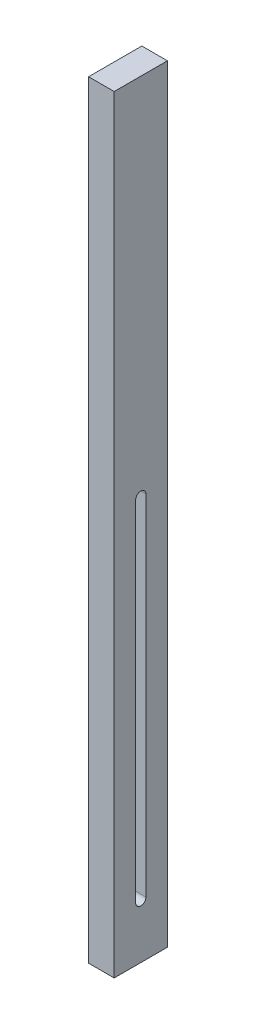
SolidWorks part; units mm, degrees
ref_plane "Front Plane" through (0, 0, 0) normal (0, 0, 1) x (1, 0, 0)
ref_plane "Top Plane" through (0, 0, 0) normal (0, 1, 0) x (1, 0, 0)
ref_plane "Right Plane" through (0, 0, 0) normal (1, 0, 0) x (0, 0, -1)
sketch "Sketch1" plane through (0, 0, 0) normal (0, 1, 0) x (1, 0, 0)
  line L1 (-101.2376, 21.9059) -> (-76.2376, 21.9059)
  line L2 (-101.2376, 21.9059) -> (-101.2376, -30.0941)
  line L3 (-101.2376, -30.0941) -> (-76.2376, -30.0941)
  line L4 (-76.2376, 21.9059) -> (-76.2376, -30.0941)
  dimension "D1" = 25
  dimension "D2" = 52
extrude "Boss-Extrude1" add sketch "Sketch1" along normal blind 750
sketch "Sketch3" plane through (-101.2376, 0, 0) normal (-1, 0, 0) x (0, 0, 1)
  line L0 (-21.9059, 750) -> (30.0941, 750)
  line L1 (4.0941, 750) -> (4.0941, 0)
  line L2 (-21.9059, 0) -> (30.0941, 0) construction
  line L3 (-0.9059, 394) -> (-0.9059, 53)
  line L4 (9.0941, 394) -> (9.0941, 53)
  line L5 (4.0941, 53) -> (4.0941, 750)
  line L6 (-0.9059, 53) -> (-0.9059, 750)
  line L7 (-0.9059, 53) -> (-0.9059, 28.9027)
  line L8 (4.0941, 750) -> (4.0941, 394)
  line L9 (4.0941, 750) -> (4.0941, 53)
  line L10 (9.0941, 53) -> (9.0941, 28.9027)
  circle A3 centre (4.0941, 394) radius 5
  circle A4 centre (4.0941, 53) radius 5
  circle A6 centre (4.0941, 28.9027) radius 5
  dimension "D1" = 750
  dimension "D2" = 697
extrude "Cut-Extrude2" cut sketch "Sketch3" against normal blind 40 contours L1 A4 | A4 L1 | A4 L4 A3 L9 | A4 L9 A3 L3 | A3 L9 L1 | L9 A3 L1
